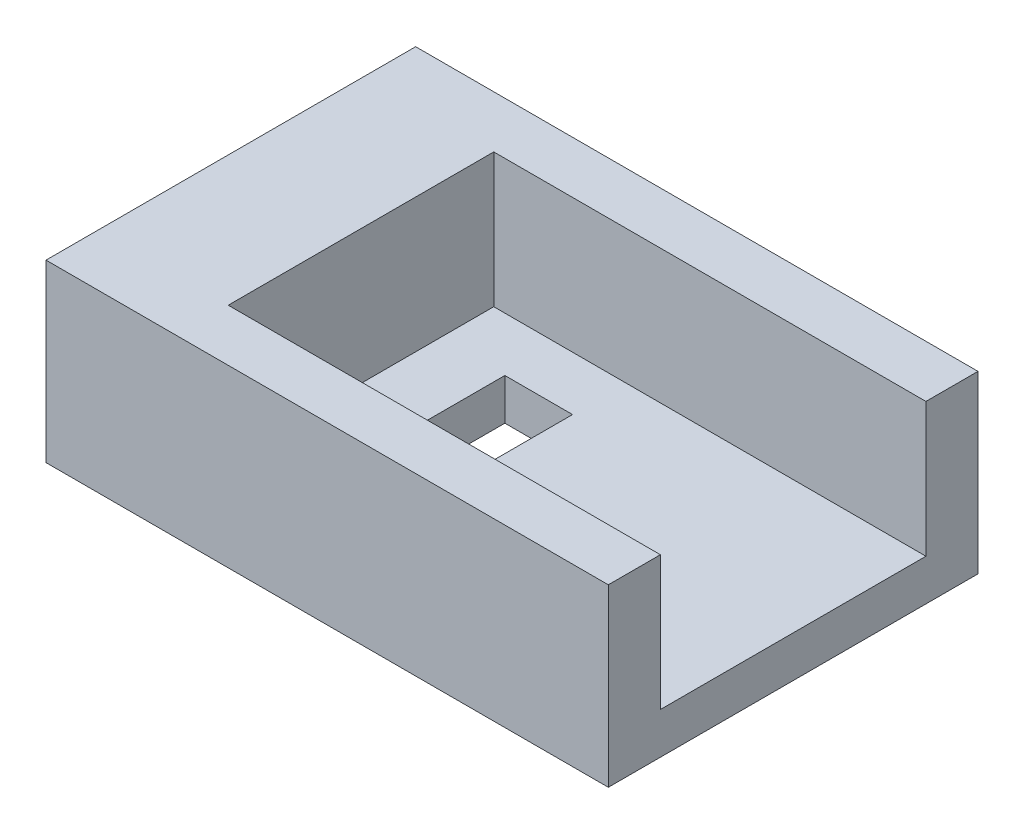
SolidWorks part; units mm, degrees
ref_plane "Front Plane" through (0, 0, 0) normal (0, 0, 1) x (1, 0, 0)
ref_plane "Top Plane" through (0, 0, 0) normal (0, 1, 0) x (1, 0, 0)
ref_plane "Right Plane" through (0, 0, 0) normal (1, 0, 0) x (0, 0, -1)
sketch "Sketch1" plane through (0, 0, 0) normal (0, 1, 0) x (1, 0, 0)
  line L1 (0, 0) -> (43.2003, 0)
  line L2 (0, 0) -> (0, 28.3997)
  line L3 (0, 28.3997) -> (43.2003, 28.3997)
  line L4 (43.2003, 0) -> (43.2003, 28.3997)
  dimension "D1" = 28.3997
  dimension "D2" = 43.2003
extrude "Boss-Extrude1" add sketch "Sketch1" along normal blind 13.4747
sketch "Sketch2" plane through (0, 13.4747, 0) normal (0, 1, 0) x (1, 0, 0)
  line L0 (43.2003, 0) -> (43.2003, 28.3997) construction
  line L1 (43.2003, 24.3992) -> (10, 24.3992)
  line L2 (43.2003, 24.3992) -> (43.2003, 4.0005)
  line L3 (43.2003, 4.0005) -> (10, 4.0005)
  line L4 (10, 24.3992) -> (10, 4.0005)
  line L5 (0, 28.3997) -> (0, 0) construction
  line L6 (0, 0) -> (43.2003, 0) construction
  dimension "D1" = 10
  dimension "D2" = 20.3987
  dimension "D3" = 4.0005
extrude "Cut-Extrude1" cut sketch "Sketch2" against normal blind 10.2997
sketch "Sketch3" plane through (0, 3.175, 0) normal (0, 1, 0) x (1, 0, 0)
  line L1 (15.0012, 20.2502) -> (20.2006, 20.2501)
  line L2 (15.0012, 20.2502) -> (15.0012, 8.1496)
  line L3 (15.0012, 8.1496) -> (20.2006, 8.1496)
  line L4 (20.2006, 20.2501) -> (20.2006, 8.1496)
  line L5 (10, 24.3992) -> (10, 4.0005) construction
  line L6 (10, 4.0005) -> (43.2003, 4.0005) construction
  dimension "D1" = 12.1006
  dimension "D2" = 5.1994
  dimension "D3" = 5.0013
  dimension "D4" = 4.1491
extrude "Cut-Extrude2" cut sketch "Sketch3" against normal through all
